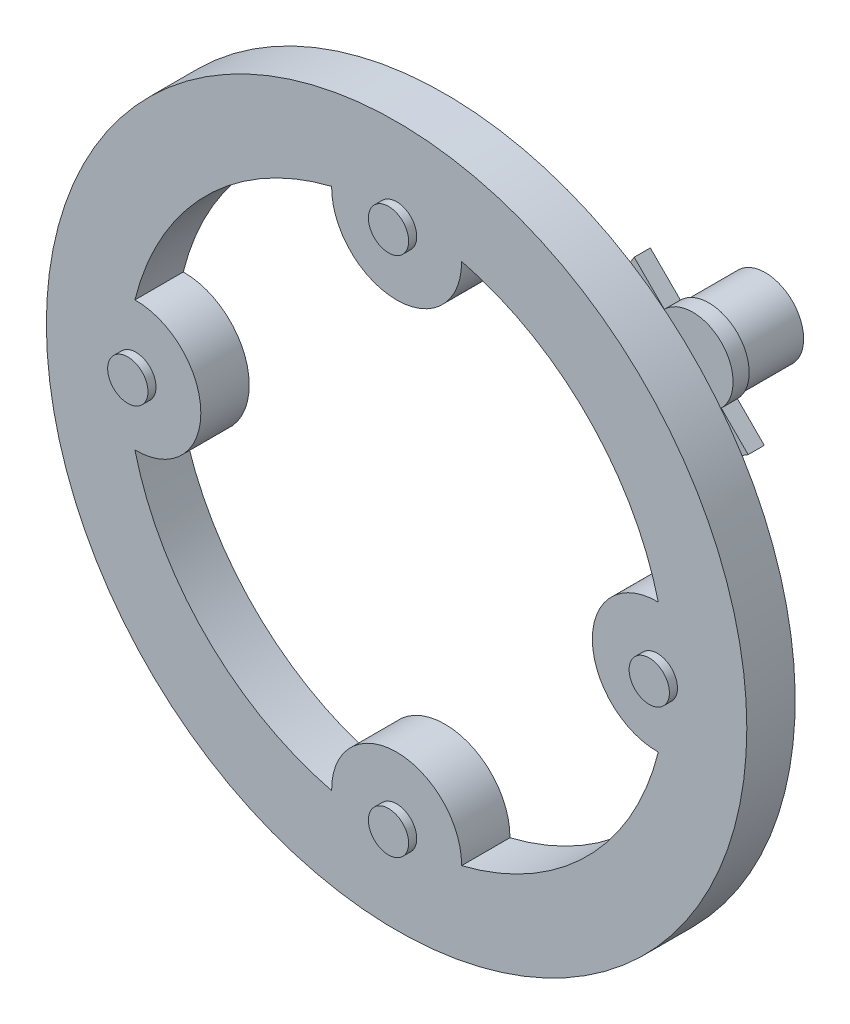
SolidWorks part; units mm, degrees
ref_plane "Front Plane" through (0, 0, 0) normal (0, 0, 1) x (1, 0, 0)
ref_plane "Top Plane" through (0, 0, 0) normal (0, 1, 0) x (1, 0, 0)
ref_plane "Right Plane" through (0, 0, 0) normal (1, 0, 0) x (0, 0, -1)
sketch "Sketch1" plane through (0, 0, 0) normal (0, 0, 1) x (1, 0, 0)
  circle A0 centre (0, 0) radius 110.363
  arc A1 (-20.4689, 82.4605) -> (-82.4605, 20.4689) centre (0, 0) ccw
  arc A2 (-20.4689, 82.4605) -> (20.4689, 82.4605) centre (0, 82.1557) ccw
  arc A3 (82.4605, 20.4689) -> (82.4605, -20.4689) centre (82.1557, 0) ccw
  arc A4 (20.4689, -82.4605) -> (-20.4689, -82.4605) centre (0, -82.1557) ccw
  arc A5 (-82.4605, -20.4689) -> (-82.4605, 20.4689) centre (-82.1557, 0) ccw
  arc A6 (82.4605, 20.4689) -> (20.4689, 82.4605) centre (0, 0) ccw
  arc A7 (20.4689, -82.4605) -> (82.4605, -20.4689) centre (0, 0) ccw
  arc A8 (-82.4605, -20.4689) -> (-20.4689, -82.4605) centre (0, 0) ccw
  point P7 (0, 61.6845)
  dimension "D1" = 220.726
  dimension "D2" = 25.4
  dimension "D3" = 4
extrude "Boss-Extrude1" add sketch "Sketch1" along normal blind 15.24
sketch "Sketch2" plane through (0, 0, 15.24) normal (0, 0, 1) x (1, 0, 0)
  circle A0 centre (0, 82.1557) radius 6.35
  circle A1 centre (82.1557, 0) radius 6.35
  circle A2 centre (0, -82.1557) radius 6.35
  circle A3 centre (-82.1557, 0) radius 6.35
  dimension "D1" = 12.7
  dimension "D2" = 4
extrude "Boss-Extrude2" add sketch "Sketch2" along normal blind 2.54
sketch "Sketch3" plane through (0, 0, 0) normal (0, 0, -1) x (-1, 0, 0)
  line L1 (-86.4737, 4.318) -> (-77.8377, 4.318)
  line L2 (-86.4737, 4.318) -> (-86.4737, -4.318)
  line L3 (-86.4737, -4.318) -> (-77.8377, -4.318)
  line L4 (-77.8377, 4.318) -> (-77.8377, -4.318)
  line L5 (-86.4737, 4.318) -> (-77.8377, -4.318) construction
  line L6 (-86.4737, -4.318) -> (-77.8377, 4.318) construction
  point P0 (-82.1557, 0)
  dimension "D1" = 8.636
  dimension "D2" = 8.636
extrude "Boss-Extrude3" add sketch "Sketch3" along normal blind 20.32
sketch "Sketch4" plane through (0, 0, 0) normal (0, 0, -1) x (-1, 0, 0)
  line L1 (-4.3561, 86.4737) -> (4.3561, 86.4737)
  line L2 (-4.3561, 86.4737) -> (-4.3561, 77.8377)
  line L3 (-4.3561, 77.8377) -> (4.3561, 77.8377)
  line L4 (4.3561, 86.4737) -> (4.3561, 77.8377)
  line L5 (-4.3561, 86.4737) -> (4.3561, 77.8377) construction
  line L6 (-4.3561, 77.8377) -> (4.3561, 86.4737) construction
  point P0 (0, 82.1557)
  dimension "D1" = 8.636
  dimension "D2" = 8.7122
extrude "Boss-Extrude4" add sketch "Sketch4" along normal blind 20.32
sketch "Sketch5" plane through (0, 0, 0) normal (0, 0, -1) x (-1, 0, 0)
  line L1 (-72.079, 44.9814) -> (-95.5489, 59.6279)
  line L2 (-44.9814, 72.079) -> (-59.6279, 95.5489)
  line L3 (-95.5489, 59.6279) -> (-59.6279, 95.5489)
  arc A2 (-20.4689, 82.4605) -> (-82.4605, 20.4689) centre (0, 0) ccw
  arc A3 (-44.9814, 72.079) -> (-72.079, 44.9814) centre (0, 0) ccw
  dimension "D1" = 0
extrude "Boss-Extrude5" add sketch "Sketch5" along normal blind 5.08
sketch "Sketch6" plane through (0, 0, -5.08) normal (0, 0, -1) x (-1, 0, 0)
  line L0 (0, 0) -> (-109.1412, 109.1412) construction
  line L1 (-59.6279, 95.5489) -> (-95.5489, 59.6279) construction
  line L2 (-87.0732, 68.1035) -> (-69.1127, 86.064)
  arc A0 (-87.0732, 68.1035) -> (-69.1127, 86.064) centre (-78.093, 77.0838) cw
  dimension "D1" = 12.7
extrude "Boss-Extrude6" add sketch "Sketch6" against normal blind 5.08
sketch "Sketch7" plane through (0, 0, -5.08) normal (0, 0, -1) x (-1, 0, 0)
  circle A0 centre (-78.093, 77.0838) radius 12.0706
extrude "Boss-Extrude7" add sketch "Sketch7" along normal blind 17.78
scale "Scale1" bodies to scale 107 scale about centroid uniform scaling yes scale factor 1
scale "Scale2" scale about centroid uniform scaling yes scale factor 1.5
